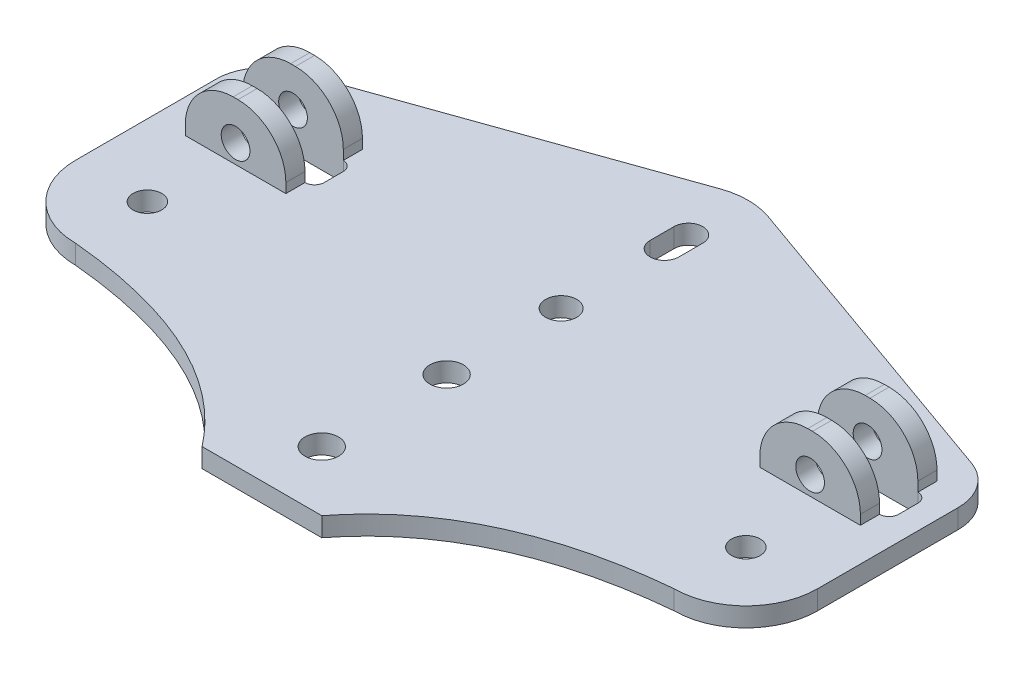
SolidWorks part; units mm, degrees
ref_plane "Front Plane" through (0, 0, 0) normal (0, 0, 1) x (1, 0, 0)
ref_plane "Top Plane" through (0, 0, 0) normal (0, 1, 0) x (1, 0, 0)
ref_plane "Right Plane" through (0, 0, 0) normal (1, 0, 0) x (0, 0, -1)
sketch "Bearing Reference" plane through (0, 0, 0) normal (0, 1, 0) x (1, 0, 0)
  line L0 (-88.9075, -9.8626) -> (103.9529, -9.8626) construction
  line L1 (-85.5461, -34.8626) -> (101.4318, -34.8626) construction
  circle A1 centre (58.784, -46.2837) radius 12
  circle A2 centre (-66.216, -46.2837) radius 12
  circle A3 centre (-3.716, 1.7163) radius 12
  point P2 (58.784, -46.2837)
  point P11 (0, 0)
  dimension "D2" = 24
  dimension "D3" = 24
  dimension "D4" = 24
  dimension "D1" = 25
  dimension "D5" = 125
  dimension "D6" = 62.5
  dimension "D7" = 48
  dimension "D8" = 48
sketch "Sketch2" plane through (0, 0, 0) normal (0, 1, 0) x (1, 0, 0)
  line L0 (-76.216, -18.3626) -> (-51.216, -26.3626) construction
  line L1 (-74.216, -18.3626) -> (-53.216, -18.3626)
  line L2 (-76.216, -20.3626) -> (-76.216, -24.3626)
  line L3 (-74.216, -26.3626) -> (-53.216, -26.3626)
  line L4 (-51.216, -20.3626) -> (-51.216, -24.3626)
  line L5 (-88.9075, -9.8626) -> (103.9529, -9.8626) construction
  line L6 (-3.716, 4.2163) -> (-3.716, -0.7837) construction
  line L7 (-88.9075, -9.8626) -> (103.9529, -9.8626) construction
  line L8 (101.4318, -34.8626) -> (-85.5461, -34.8626) construction
  line L9 (-66.216, -46.2837) -> (58.784, -46.2837) construction
  line L10 (-3.716, -46.2837) -> (-3.716, 1.7163) construction
  line L11 (66.784, -26.3626) -> (45.784, -26.3626)
  line L12 (43.784, -20.3626) -> (43.784, -24.3626)
  line L13 (66.784, -18.3626) -> (45.784, -18.3626)
  line L14 (68.784, -20.3626) -> (68.784, -24.3626)
  line L15 (-81.216, -46.2837) -> (-81.216, -16.9256)
  line L16 (-74.5595, -7.5011) -> (-8.7313, 15.853)
  line L17 (73.784, -46.2837) -> (73.784, -16.9256)
  line L18 (67.1276, -7.5011) -> (1.2994, 15.853)
  line L19 (-16.216, -34.8626) -> (8.784, -34.8626) construction
  line L20 (-16.216, -22.3626) -> (8.784, -22.3626) construction
  line L21 (-16.216, -22.3626) -> (-16.216, -72.3626) construction
  line L22 (-16.216, -72.3626) -> (8.784, -72.3626) construction
  line L23 (8.784, -22.3626) -> (8.784, -72.3626) construction
  line L24 (-16.216, -34.8626) -> (-16.216, -84.8626) construction
  line L25 (-16.216, -84.8626) -> (8.784, -84.8626)
  line L26 (8.784, -34.8626) -> (8.784, -84.8626) construction
  line L27 (-0.716, 4.2163) -> (-0.716, -0.7837)
  line L28 (-6.716, 4.2163) -> (-6.716, -0.7837)
  arc A0 (-81.216, -46.2837) -> (-66.216, -61.2837) centre (-66.216, -46.2837) ccw
  arc A1 (1.2994, 15.853) -> (-8.7313, 15.853) centre (-3.716, 1.7163) ccw
  arc A2 (58.784, -61.2837) -> (73.784, -46.2837) centre (58.784, -46.2837) ccw
  circle A3 centre (-66.216, -46.2837) radius 3
  circle A4 centre (58.784, -46.2837) radius 3
  arc A6 (73.784, -16.9256) -> (67.1276, -7.5011) centre (63.784, -16.9256) ccw
  arc A7 (-81.216, -16.9256) -> (-74.5595, -7.5011) centre (-71.216, -16.9256) cw
  arc A8 (66.784, -18.3626) -> (68.784, -20.3626) centre (66.784, -20.3626) cw
  arc A9 (66.784, -26.3626) -> (68.784, -24.3626) centre (66.784, -24.3626) ccw
  arc A10 (45.784, -26.3626) -> (43.784, -24.3626) centre (45.784, -24.3626) cw
  arc A11 (43.784, -20.3626) -> (45.784, -18.3626) centre (45.784, -20.3626) cw
  arc A12 (-53.216, -26.3626) -> (-51.216, -24.3626) centre (-53.216, -24.3626) ccw
  arc A13 (-53.216, -18.3626) -> (-51.216, -20.3626) centre (-53.216, -20.3626) cw
  arc A14 (-74.216, -18.3626) -> (-76.216, -20.3626) centre (-74.216, -20.3626) ccw
  arc A15 (-76.216, -24.3626) -> (-74.216, -26.3626) centre (-74.216, -24.3626) ccw
  arc A16 (-0.716, 4.2163) -> (-6.716, 4.2163) centre (-3.716, 4.2163) ccw
  arc A17 (-6.716, -0.7837) -> (-0.716, -0.7837) centre (-3.716, -0.7837) ccw
  circle A18 centre (-3.716, -22.3626) radius 3.25
  circle A19 centre (-3.716, -46.2837) radius 3.5
  circle A20 centre (-3.716, -72.3626) radius 3.5
  spline S0 degree 2 poles (-66.216, -61.2837) (-31.9884, -64.4698) (-16.216, -84.8626) knots 0 0 0 0.615675 0.615675 0.615675
  spline S1 degree 2 poles (58.784, -61.2837) (24.5565, -64.4698) (8.784, -84.8626) knots 0 0 0 0.615675 0.615675 0.615675
  point P7 (68.784, -18.3626)
  point P51 (73.784, -9.8626)
  point P54 (-81.216, -9.8626)
  point P56 (68.784, -26.3626)
  point P59 (43.784, -26.3626)
  point P62 (43.784, -18.3626)
  point P68 (-51.216, -18.3626)
  point P74 (-76.216, -26.3626)
  point P75 (-3.716, 1.7163)
  dimension "D1" = 30
  dimension "D2" = 30
  dimension "D3" = 30
  dimension "D8" = 6
  dimension "D9" = 6.5
  dimension "D10" = 6
  dimension "D15" = 10
  dimension "D17" = 2
  dimension "D19" = 3
  dimension "D20" = 7
  dimension "D21" = 7
  dimension "D4" = 8
  dimension "D5" = 25
  dimension "D6" = 8.5
  dimension "D7" = 10
  dimension "D11" = 25
  dimension "D12" = 50
  dimension "D13" = 12.5
  dimension "D14" = 50
  dimension "D16" = 25
  dimension "D18" = 5
  dimension "D22" = 12.5
extrude "MainPlateExtrude" add sketch "Sketch2" along normal blind 4
sketch "Sketch3" plane through (0, 4, 0) normal (0, 1, 0) x (1, 0, 0)
  line L0 (-74.216, -18.3626) -> (-53.216, -18.3626)
  line L1 (-74.216, -18.3626) -> (-74.216, -14.3626)
  line L2 (-53.216, -18.3626) -> (-53.216, -14.3626)
  line L3 (-74.216, -14.3626) -> (-53.216, -14.3626)
  line L4 (-74.216, -26.3626) -> (-53.216, -26.3626)
  line L5 (-74.216, -26.3626) -> (-74.216, -30.3626)
  line L6 (-53.216, -26.3626) -> (-53.216, -30.3626)
  line L7 (-74.216, -30.3626) -> (-53.216, -30.3626)
  line L8 (-3.716, 16.7163) -> (-3.716, -84.8626) construction
  line L9 (-16.216, -84.8626) -> (8.784, -84.8626) construction
  line L10 (45.784, -26.3626) -> (45.784, -30.3626)
  line L11 (66.784, -30.3626) -> (45.784, -30.3626)
  line L12 (66.784, -26.3626) -> (66.784, -30.3626)
  line L13 (66.784, -26.3626) -> (45.784, -26.3626)
  line L14 (45.784, -18.3626) -> (45.784, -14.3626)
  line L15 (66.784, -14.3626) -> (45.784, -14.3626)
  line L16 (66.784, -18.3626) -> (66.784, -14.3626)
  line L17 (66.784, -18.3626) -> (45.784, -18.3626)
  arc A0 (1.2994, 15.853) -> (-8.7313, 15.853) centre (-3.716, 1.7163) ccw construction
  dimension "D1" = 4
  dimension "D2" = 4
extrude "TopBearing" add sketch "Sketch3" along normal blind 12
fillet "Fillet1" radius 10 8 edges at (66.784, 16, 16.3626) (66.784, 16, 28.3626) (45.784, 16, 16.3626) (45.784, 16, 28.3626) (-53.216, 16, 16.3626) (-53.216, 16, 28.3626) (-74.216, 16, 16.3626) (-74.216, 16, 28.3626)
sketch "Sketch4" plane through (0, 0, 30.3626) normal (0, 0, 1) x (1, 0, 0)
  line L0 (-79.7629, -4) -> (-37.0465, -4) construction
  line L1 (-81.216, 0) -> (-66.216, 0) construction
  line L2 (-63.716, 16) -> (-63.716, -14.1952) construction
  line L3 (-64.216, 16) -> (-63.216, 16) construction
  line L4 (-3.716, 4) -> (-3.716, 0) construction
  line L5 (-16.216, 4) -> (8.784, 4) construction
  line L6 (-16.216, 0) -> (8.784, 0) construction
  circle A0 centre (-63.716, 7.9274) radius 12 construction
  circle A1 centre (-63.716, 7.9274) radius 3
  circle A2 centre (56.284, 7.9274) radius 3
  point P19 (0, 0)
  dimension "D1" = 24
  dimension "D3" = 6
  dimension "D2" = 4
extrude "TopBearingCut" cut sketch "Sketch4" against normal up to surface (16 mm away) up to face at (-63.716, 9.357, 14.3626)
